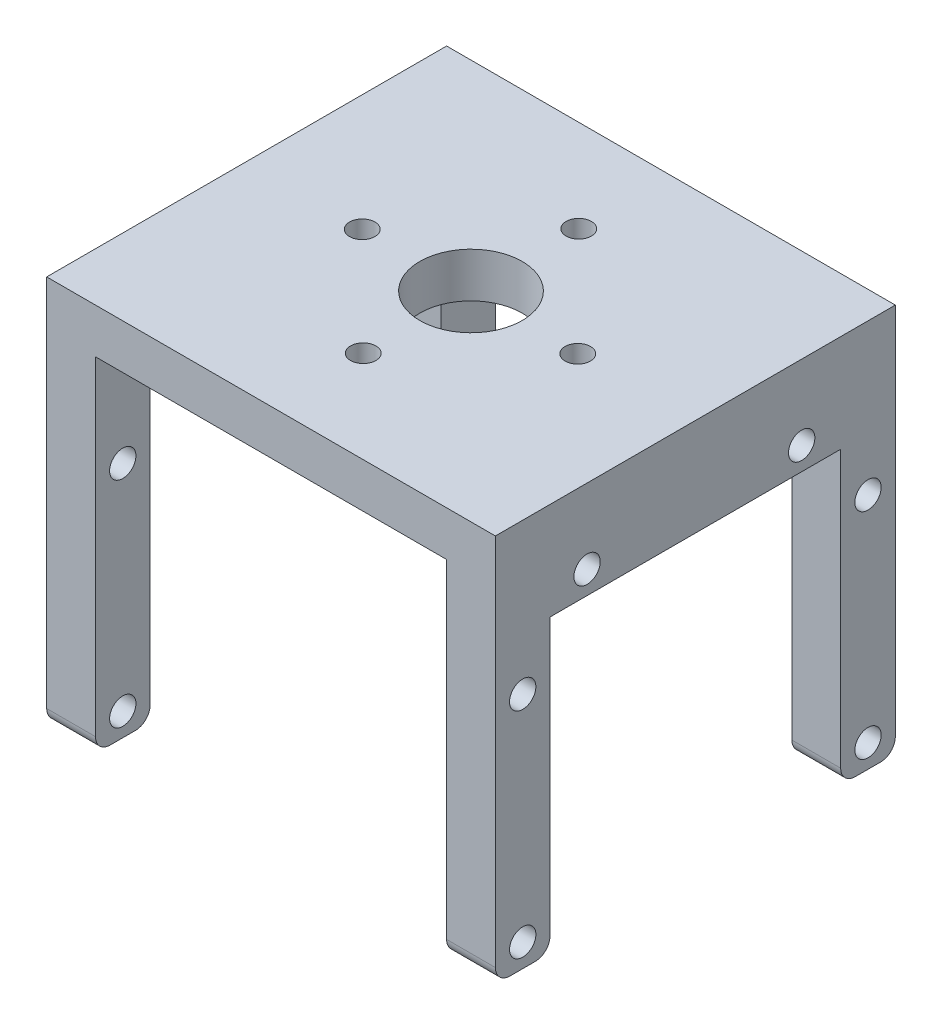
SolidWorks part; units mm, degrees
ref_plane "Front Plane" through (0, 0, 0) normal (0, 0, 1) x (1, 0, 0)
ref_plane "Top Plane" through (0, 0, 0) normal (0, 1, 0) x (1, 0, 0)
ref_plane "Right Plane" through (0, 0, 0) normal (1, 0, 0) x (0, 0, -1)
sketch "Sketch1" plane through (0, 0, 0) normal (0, 0, 1) x (1, 0, 0)
  line L0 (-17.875, 0.2462) -> (-12.875, 0.2462)
  line L1 (-12.875, 0.2462) -> (-12.875, 5.6562)
  line L2 (-12.875, 5.6562) -> (23.125, 5.6562)
  line L3 (23.125, 5.6562) -> (23.125, 0.2462)
  line L4 (23.125, 0.2462) -> (28.125, 0.2462)
  line L5 (28.125, 0.2462) -> (28.125, 10.2462)
  line L6 (28.125, 10.2462) -> (-17.875, 10.2462)
  line L7 (-17.875, 10.2462) -> (-17.875, 0.2462)
  dimension "D1" = 5
  dimension "D2" = 5
  dimension "D3" = 5.41
  dimension "D4" = 5.41
  dimension "D5" = 4.59
  dimension "D6" = 36
extrude "Boss-Extrude1" add sketch "Sketch1" along normal blind 41
sketch "Sketch2" plane through (0, 0.2462, 0) normal (0, -1, 0) x (1, 0, 0)
  line L0 (-12.875, 41) -> (-12.875, 0) construction
  line L1 (-17.875, 0) -> (-12.875, 0)
  line L2 (-17.875, 0) -> (-17.875, 5.6)
  line L3 (-17.875, 5.6) -> (-12.875, 5.6)
  line L4 (-12.875, 0) -> (-12.875, 5.6)
  line L5 (23.125, 41) -> (23.125, 0) construction
  line L6 (-17.875, 41) -> (-12.875, 41)
  line L7 (-17.875, 41) -> (-17.875, 35.4)
  line L8 (-17.875, 35.4) -> (-12.875, 35.4)
  line L9 (-12.875, 41) -> (-12.875, 35.4)
  line L10 (28.125, 41) -> (23.125, 41)
  line L11 (28.125, 41) -> (28.125, 35.4)
  line L12 (28.125, 35.4) -> (23.125, 35.4)
  line L13 (23.125, 41) -> (23.125, 35.4)
  line L15 (28.125, 0) -> (23.125, 0)
  line L16 (28.125, 0) -> (28.125, 5.6)
  line L17 (28.125, 5.6) -> (23.125, 5.6)
  line L18 (23.125, 0) -> (23.125, 5.6)
  dimension "D1" = 5.6
  dimension "D2" = 5.6
  dimension "D3" = 5.6
  dimension "D4" = 5.6
extrude "Boss-Extrude2" add sketch "Sketch2" along normal blind 29.82
fillet "Fillet1" radius 1.5 8 edges at (25.625, -29.5738, 5.6) (25.625, -29.5738, 0) (-15.375, -29.5738, 5.6) (-15.375, -29.5738, 0) (-15.375, -29.5738, 35.4) (-15.375, -29.5738, 41) (25.625, -29.5738, 41) (25.625, -29.5738, 35.4)
sketch "Sketch3" plane through (-17.875, 0, 0) normal (-1, 0, 0) x (0, 0, 1)
  line L0 (39.5, -29.5737) -> (36.9, -29.5737) construction
  line L1 (35.4, -28.0737) -> (35.4, 0.2463) construction
  line L2 (5.6, -28.0737) -> (5.6, 0.2463) construction
  line L3 (4.1, -29.5737) -> (1.5, -29.5737) construction
  line L4 (41, 10.2462) -> (41, -28.0737) construction
  line L5 (0, 10.2462) -> (0, -28.0737) construction
  circle A0 centre (38.2, -27.2037) radius 1.35
  circle A1 centre (2.8, -27.2037) radius 1.35
  circle A2 centre (38.2, -5.2037) radius 1.35
  circle A3 centre (2.8, -5.2037) radius 1.35
  dimension "D1" = 2.37
  dimension "D2" = 2.8
  dimension "D3" = 2.8
  dimension "D4" = 2.37
  dimension "D5" = 2.7
  dimension "D6" = 2.7
  dimension "D7" = 22
  dimension "D8" = 2.7
  dimension "D9" = 2.7
  dimension "D10" = 22
  dimension "D11" = 2.8
  dimension "D12" = 2.8
extrude "Cut-Extrude1" cut sketch "Sketch3" against normal blind 49
sketch "Sketch4" plane through (28.125, 0, 0) normal (1, 0, 0) x (0, 0, -1)
  line L0 (-35.4, 0.2462) -> (-5.6, 0.2462) construction
  line L1 (0, -28.0738) -> (0, 10.2462) construction
  circle A0 centre (-9.6, 2.5962) radius 1.35
  circle A1 centre (-31.6, 2.5962) radius 1.35
  point P6 (-20.6, 2.5962)
  dimension "D1" = 2.7
  dimension "D2" = 2.7
  dimension "D4" = 2.35
  dimension "D5" = 22
  dimension "D6" = 11
  dimension "D3" = 2.35
  dimension "D7" = 20.6
extrude "Cut-Extrude2" cut sketch "Sketch4" against normal blind 49
sketch "Sketch5" plane through (0, 10.2462, 0) normal (0, 1, 0) x (1, 0, 0)
  line L0 (5.125, 0) -> (5.125, -41)
  line L1 (28.125, 0) -> (-17.875, 0) construction
  line L2 (28.125, -41) -> (-17.875, -41) construction
  line L3 (28.125, -41) -> (28.125, 0) construction
  line L4 (28.125, -20.5) -> (-17.875, -20.5)
  line L5 (-17.875, -41) -> (-17.875, 0) construction
  circle A1 centre (5.125, -9.45) radius 1.3
  circle A2 centre (-5.9245, -20.6) radius 1.3
  circle A3 centre (5.125, -31.55) radius 1.3
  circle A4 centre (16.1745, -20.6) radius 1.3
  circle A5 centre (5.125, -20.5) radius 5.25
  dimension "D1" = 11.05
  dimension "D2" = 11.05
  dimension "D3" = 11.05
  dimension "D4" = 11.05
  dimension "D5" = 10.5
  dimension "D6" = 2.6
  dimension "D7" = 2.6
  dimension "D8" = 2.6
  dimension "D9" = 2.6
extrude "Cut-Extrude3" cut sketch "Sketch5" against normal blind 7 contours A2 | A5 | A3 | A4 | A1
